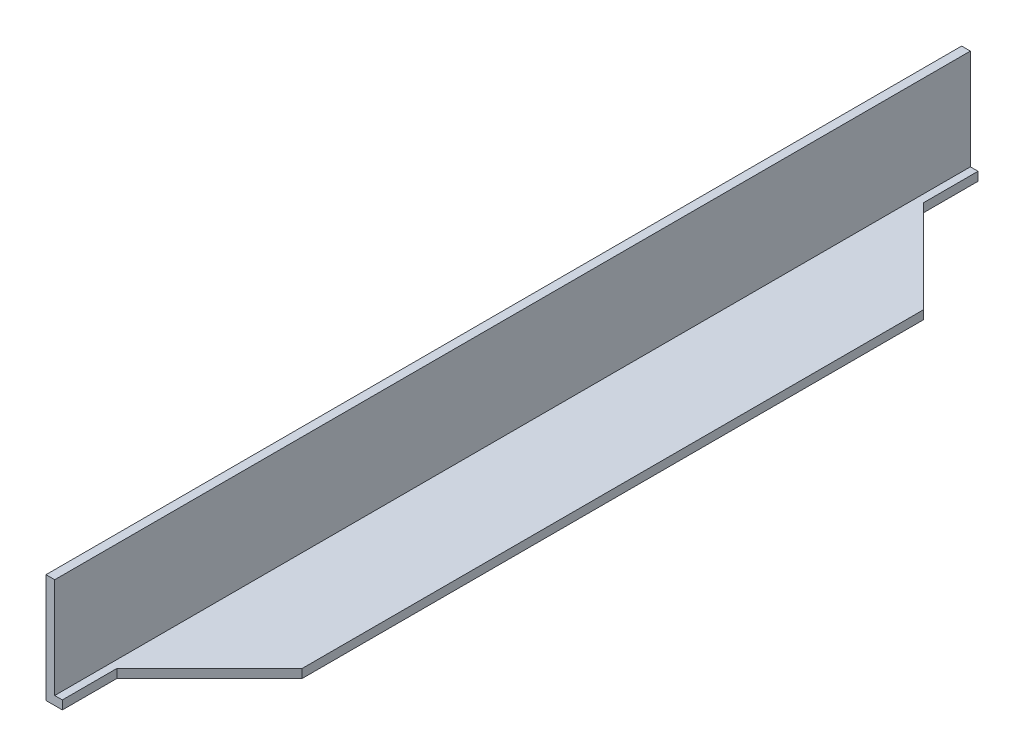
SolidWorks part; units mm, degrees
ref_plane "前视基准面" through (0, 0, 0) normal (0, 0, 1) x (1, 0, 0)
ref_plane "上视基准面" through (0, 0, 0) normal (0, 1, 0) x (1, 0, 0)
ref_plane "右视基准面" through (0, 0, 0) normal (1, 0, 0) x (0, 0, -1)
sketch "草图1" plane through (0, 0, 0) normal (0, 0, 1) x (1, 0, 0)
  line L1 (0, 0) -> (100, 0)
  line L2 (0, 0) -> (0, 100)
  line L3 (0, 100) -> (100, 100)
  line L4 (100, 0) -> (100, 100)
  dimension "D1" = 100
  dimension "D2" = 100
extrude "凸台-拉伸1" add sketch "草图1" along normal blind 840
sketch "草图2" plane through (0, 0, 840) normal (0, 0, 1) x (1, 0, 0)
  line L0 (0, 100) -> (0, 0) construction
  line L1 (100, 100) -> (8, 100)
  line L2 (100, 100) -> (100, 8)
  line L3 (100, 8) -> (8, 8)
  line L4 (8, 100) -> (8, 8)
  line L5 (0, 0) -> (100, 0) construction
  dimension "D1" = 8
  dimension "D2" = 8
extrude "切除-拉伸1" cut sketch "草图2" against normal through all
sketch "草图4" plane through (0, 8, 0) normal (0, 1, 0) x (1, 0, 0)
  line L0 (15, 0) -> (15, -50)
  line L1 (8, 0) -> (100, 0) construction
  line L2 (15, -50) -> (100, -135)
  line L3 (100, 0) -> (100, -840) construction
  line L4 (100, -135) -> (100, 0)
  line L5 (100, 0) -> (15, 0)
  line L6 (15, -840) -> (15, -790)
  line L7 (8, -840) -> (100, -840) construction
  line L8 (15, -790) -> (100, -705)
  line L9 (100, -705) -> (100, -840)
  line L10 (100, -840) -> (15, -840)
  line L11 (0, -840) -> (0, 0) construction
  dimension "D1" = 15
  dimension "D2" = 50
  dimension "D3" = 45
extrude "切除-拉伸3" cut sketch "草图4" against normal through all
